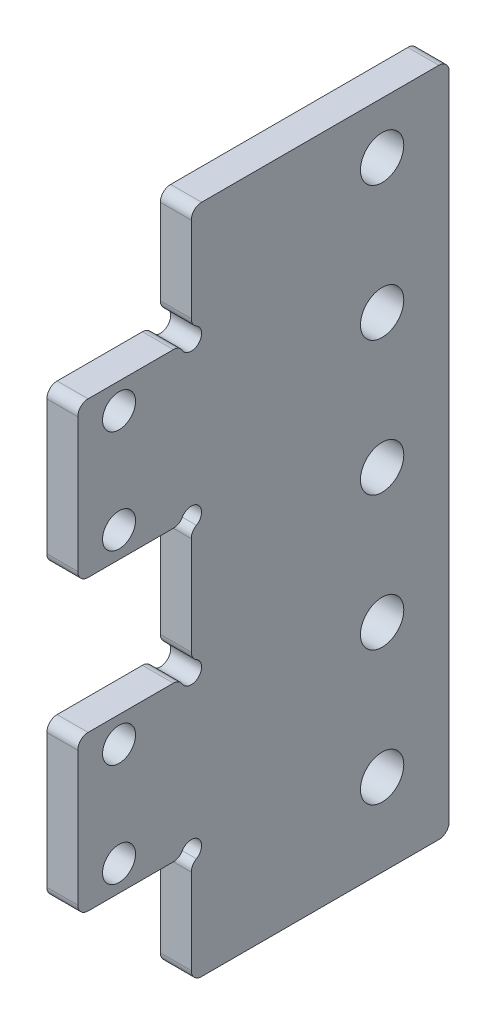
SolidWorks part; units mm, degrees
ref_plane "前视基准面" through (0, 0, 0) normal (0, 0, 1) x (1, 0, 0)
ref_plane "上视基准面" through (0, 0, 0) normal (0, 1, 0) x (1, 0, 0)
ref_plane "右视基准面" through (0, 0, 0) normal (1, 0, 0) x (0, 0, -1)
other "Configuration Table"
sketch "草图1" plane through (0, 0, 0) normal (1, 0, 0) x (0, 0, -1)
  line L1 (0, 0) -> (28, 0)
  line L2 (0, 0) -> (0, 65)
  line L3 (0, 65) -> (28, 65)
  line L4 (28, 0) -> (28, 65)
  dimension "D1" = 65
  dimension "D2" = 28
extrude "凸台-拉伸1" add sketch "草图1" along normal blind 3
sketch "草图2" plane through (3, 0, 0) normal (1, 0, 0) x (0, 0, -1)
  line L0 (0, 65) -> (0, 0) construction
  line L1 (0, 65) -> (3, 65)
  line L2 (0, 65) -> (0, 54)
  line L3 (0, 54) -> (3, 54)
  line L4 (3, 65) -> (3, 54)
  line L5 (0, 39) -> (3, 39)
  line L6 (0, 39) -> (0, 26)
  line L7 (0, 26) -> (3, 26)
  line L8 (3, 39) -> (3, 26)
  line L10 (0, 0) -> (3, 0)
  line L11 (0, 0) -> (0, 11)
  line L12 (0, 11) -> (3, 11)
  line L13 (3, 0) -> (3, 11)
  dimension "D1" = 3
  dimension "D2" = 15
  dimension "D3" = 11
  dimension "D4" = 13
  dimension "D5" = 15
extrude "切除-拉伸1" cut sketch "草图2" against normal through all
sketch "草图3" plane through (3, 0, 0) normal (1, 0, 0) x (0, 0, -1)
  line L0 (21.5, 65) -> (21.5, 0) construction
  line L1 (28, 65) -> (3, 65) construction
  line L2 (3, 0) -> (28, 0) construction
  line L3 (3, 26) -> (3, 39) construction
  circle A0 centre (21.5, 60) radius 2.1
  circle A5 centre (21.5, 47) radius 2.1
  circle A6 centre (21.5, 34) radius 2.1
  circle A7 centre (21.5, 21) radius 2.1
  circle A8 centre (21.5, 8) radius 2.1
  dimension "D2" = 4.2
  dimension "D3" = 5
  dimension "D5" = 13
  dimension "D1" = 18.5
  dimension "D4" = 5
extrude "切除-拉伸2" cut sketch "草图3" against normal through all
sketch "草图4" plane through (3, 0, 0) normal (1, 0, 0) x (0, 0, -1)
  circle A0 centre (3, 54) radius 1
  circle A1 centre (3, 39) radius 1
  circle A2 centre (3, 26) radius 1
  circle A3 centre (3, 11) radius 1
  dimension "D1" = 2
extrude "切除-拉伸3" cut sketch "草图4" against normal through all
sketch "草图5" plane through (0, 0, 0) normal (0, 0, 1) x (1, 0, 0)
  line L0 (3, 11) -> (3, 26) construction
  line L1 (3, 26) -> (0, 26) construction
  line L2 (0, 26) -> (0, 11) construction
  line L3 (0, 11) -> (3, 11) construction
  line L4 (3, 39) -> (3, 54) construction
  line L5 (3, 54) -> (0, 54) construction
  line L6 (0, 54) -> (0, 39) construction
  line L7 (0, 39) -> (3, 39) construction
  line L8 (3, 11) -> (3, 26)
  line L9 (3, 26) -> (0, 26)
  line L10 (0, 26) -> (0, 11)
  line L11 (0, 11) -> (3, 11)
  line L12 (3, 39) -> (3, 54)
  line L13 (3, 54) -> (0, 54)
  line L14 (0, 54) -> (0, 39)
  line L15 (0, 39) -> (3, 39)
extrude "凸台-拉伸2" add sketch "草图5" along normal blind 8
sketch "草图6" plane through (3, 0, 0) normal (1, 0, 0) x (0, 0, -1)
  line L0 (-4, 54) -> (-4, 11) construction
  line L1 (-8, 54) -> (2, 54) construction
  line L2 (2, 11) -> (-8, 11) construction
  line L3 (-8, 39) -> (-8, 54) construction
  line L4 (-8, 26) -> (2, 26) construction
  circle A0 centre (-4, 51.5) radius 1.6
  circle A1 centre (-4, 41.5) radius 1.6
  circle A2 centre (-4, 23.5) radius 1.6
  circle A3 centre (-4, 13.5) radius 1.6
  dimension "D2" = 3.2
  dimension "D3" = 10
  dimension "D4" = 10
  dimension "D5" = 2.5
  dimension "D6" = 2.5
  dimension "D1" = 4
extrude "切除-拉伸4" cut sketch "草图6" against normal blind 10
fillet "圆角1" radius 1 16 edges at (1.5, 54, -2) (1.5, 54, 8) (1.5, 39, 8) (1.5, 39, -2) (1.5, 38, -3) (1.5, 27, -3) (1.5, 26, -2) (1.5, 26, 8) (1.5, 11, 8) (1.5, 11, -2) (1.5, 10, -3) (1.5, 0, -3) (1.5, 0, -28) (1.5, 65, -28) (1.5, 55, -3) (1.5, 65, -3)
